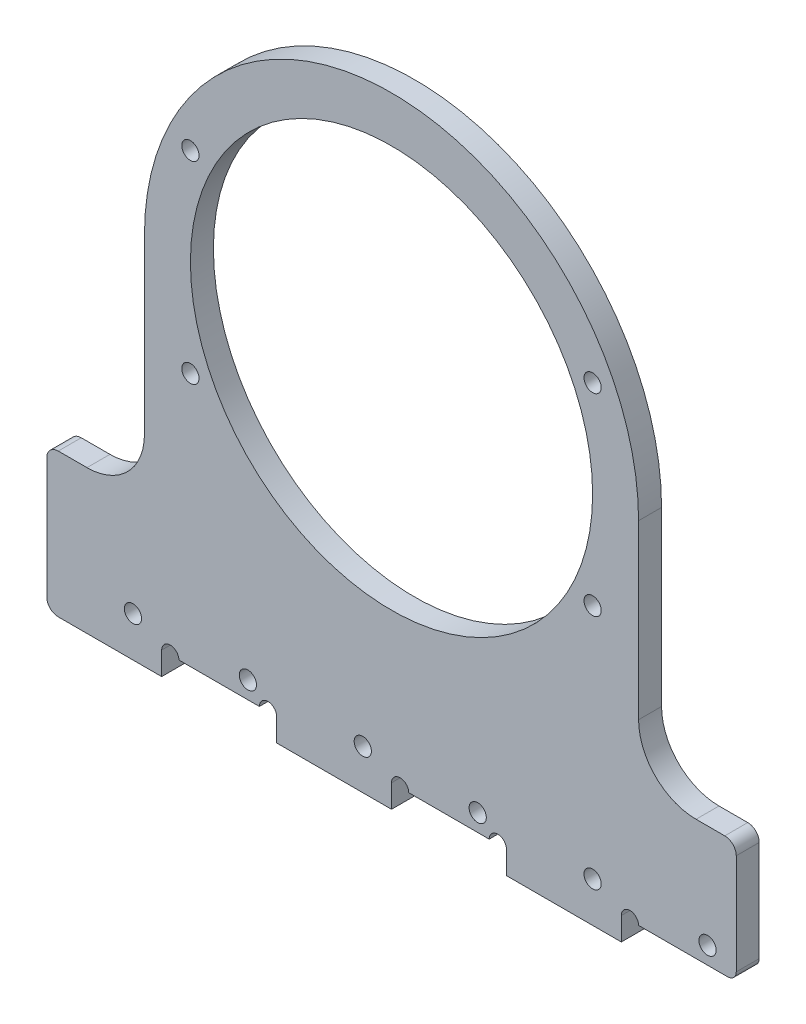
SolidWorks part; units mm, degrees
ref_plane "前视基准面" through (0, 0, 0) normal (0, 0, 1) x (1, 0, 0)
ref_plane "上视基准面" through (0, 0, 0) normal (0, 1, 0) x (1, 0, 0)
ref_plane "右视基准面" through (0, 0, 0) normal (1, 0, 0) x (0, 0, -1)
other "Configuration Table"
sketch "草图1" plane through (0, 0, 0) normal (0, 0, 1) x (1, 0, 0)
  line L0 (-43, 0) -> (-43, -40)
  line L1 (-43, -40) -> (-60, -40)
  line L2 (-60, -40) -> (-60, -65)
  line L3 (-60, -65) -> (60, -65)
  line L4 (60, -65) -> (60, -40)
  line L5 (60, -40) -> (43, -40)
  line L6 (43, -40) -> (43, 0)
  circle A0 centre (0, 0) radius 43
  circle A1 centre (0, 0) radius 35
  dimension "D1" = 70
  dimension "D2" = 86
  dimension "D3" = 120
  dimension "D4" = 40
  dimension "D6" = 25
extrude "凸台-拉伸1" add sketch "草图1" along normal blind 4 contours A0 A1 | A0 L0 L1 L2 L3 L4 L5 L6
sketch "草图2" plane through (0, 0, 4) normal (0, 0, 1) x (1, 0, 0)
  line L1 (-35, 16.8) -> (35, 16.8) construction
  line L2 (-35, 16.8) -> (-35, -16.8) construction
  line L3 (-35, -16.8) -> (35, -16.8) construction
  line L4 (35, 16.8) -> (35, -16.8) construction
  line L5 (-35, 16.8) -> (35, -16.8) construction
  line L6 (-35, -16.8) -> (35, 16.8) construction
  circle A0 centre (-35, 16.8) radius 1.5
  circle A1 centre (-35, -16.8) radius 1.5
  circle A2 centre (35, -16.8) radius 1.5
  circle A3 centre (35, 16.8) radius 1.5
  point P0 (0, 0)
  dimension "D3" = 3
  dimension "D4" = 3
  dimension "D5" = 3
  dimension "D6" = 3
  dimension "D1" = 33.6
  dimension "D2" = 70
extrude "切除-拉伸1" cut sketch "草图2" against normal blind 10
fillet "圆角1" radius 10 2 edges at (-43, -40, 2) (43, -40, 2)
fillet "圆角2" radius 2 4 edges at (60, -65, 2) (-60, -65, 2) (-60, -40, 2) (60, -40, 2)
sketch "草图3" plane through (0, 0, 4) normal (0, 0, 1) x (1, 0, 0)
  line L0 (-58, -65) -> (58, -65) construction
  line L1 (-40, -65) -> (-20, -65)
  line L2 (-40, -65) -> (-40, -61)
  line L3 (-40, -61) -> (-20, -61)
  line L4 (-20, -65) -> (-20, -61)
  line L5 (60, -65) -> (40, -65)
  line L6 (60, -65) -> (60, -61)
  line L7 (60, -61) -> (40, -61)
  line L8 (40, -65) -> (40, -61)
  line L9 (20, -65) -> (0, -65)
  line L10 (20, -65) -> (20, -61)
  line L11 (20, -61) -> (0, -61)
  line L12 (0, -65) -> (0, -61)
  line L13 (60, -63) -> (60, -42) construction
  arc A0 (40, -61) -> (43, -61) centre (41.5, -61) cw
  arc A1 (20, -61) -> (17, -61) centre (18.5, -61) ccw
  arc A2 (0, -61) -> (3, -61) centre (1.5, -61) cw
  arc A3 (-40, -61) -> (-37, -61) centre (-38.5, -61) cw
  arc A4 (-20, -61) -> (-23, -61) centre (-21.5, -61) ccw
  line M10 (-58, -65) -> (58, -65)
  arc M11 (58, -65) -> (60, -63) centre (58, -63) ccw
  line M12 (60, -63) -> (60, -42)
  dimension "D7" = 1.5
  dimension "D8" = 1.5
  dimension "D9" = 1.5
  dimension "D10" = 1.5
  dimension "D11" = 1.5
  dimension "D1" = 20
  dimension "D2" = 20
  dimension "D3" = 20
  dimension "D4" = 20
  dimension "D5" = 20
  dimension "D6" = 4
extrude "切除-拉伸2" cut sketch "草图3" against normal blind 10 contours L4 L3 L2 M10 | A3 L3 | L3 A4 | A2 L11 | L12 L10 L11 M10 | L11 A1 | A0 L7 | L8 L7 M10 M11 M12
fillet "圆角3" radius 1.5 1 edges at (60, -61, 2)
sketch "草图4" plane through (0, 0, 0) normal (0, 0, -1) x (-1, 0, 0)
  line L0 (-58.5, -61) -> (-43, -61) construction
  line L1 (-60, -59.5) -> (-60, -42) construction
  line L2 (-55, -58) -> (-35, -58) construction
  circle A0 centre (-55, -58) radius 1.5
  circle A1 centre (-35, -58) radius 1.5
  circle A2 centre (-15, -58) radius 1.5
  circle A3 centre (5, -58) radius 1.5
  circle A4 centre (25, -58) radius 1.5
  circle A5 centre (45, -58) radius 1.5
  dimension "D1" = 3
  dimension "D2" = 3
  dimension "D3" = 5
  dimension "D5" = 20
  dimension "D4" = 6
extrude "切除-拉伸3" cut sketch "草图4" against normal blind 4
